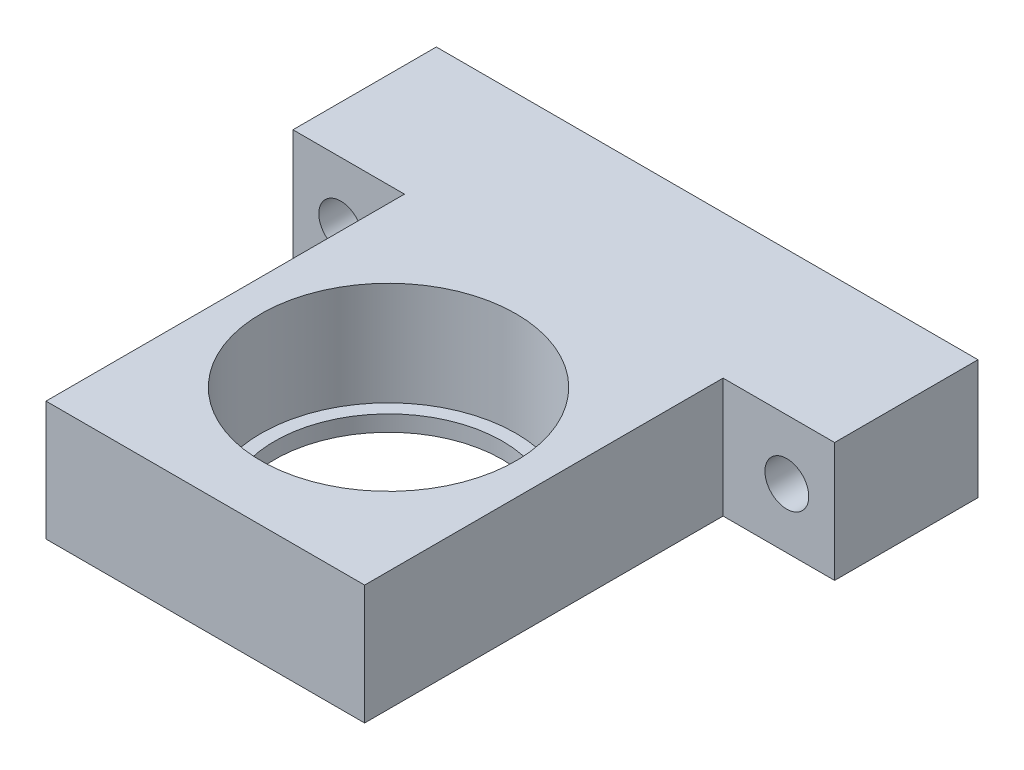
SolidWorks part; units mm, degrees
ref_plane "前视基准面" through (0, 0, 0) normal (0, 0, 1) x (1, 0, 0)
ref_plane "上视基准面" through (0, 0, 0) normal (0, 1, 0) x (1, 0, 0)
ref_plane "右视基准面" through (0, 0, 0) normal (1, 0, 0) x (0, 0, -1)
sketch "草图1" plane through (0, 0, 0) normal (0, 0, 1) x (1, 0, 0)
  line L1 (-34, 7.5) -> (34, 7.5)
  line L2 (-34, 7.5) -> (-34, -7.5)
  line L3 (-34, -7.5) -> (34, -7.5)
  line L4 (34, 7.5) -> (34, -7.5)
  line L5 (0, -7.5) -> (0, 7.5) construction
  line L6 (-34, 0) -> (34, 0) construction
  point P0 (0, 0)
  dimension "D1" = 15
  dimension "D2" = 68
extrude "凸台-拉伸1" add sketch "草图1" along normal blind 18
sketch "草图2" plane through (0, 0, 18) normal (0, 0, 1) x (1, 0, 0)
  line L0 (-34, -7.5) -> (34, -7.5) construction
  line L1 (-20, 7.5) -> (20, 7.5)
  line L2 (-20, 7.5) -> (-20, -7.5)
  line L3 (-20, -7.5) -> (20, -7.5)
  line L4 (20, 7.5) -> (20, -7.5)
  line L5 (0, -7.5) -> (0, 7.5) construction
  line L6 (-20, 0) -> (20, 0) construction
  point P0 (0, 0)
  dimension "D1" = 40
extrude "凸台-拉伸2" add sketch "草图2" along normal blind 45
sketch "草图3" plane through (0, -7.5, 0) normal (0, -1, 0) x (1, 0, 0)
  circle A0 centre (0, 40) radius 16
  dimension "D2" = 32
  dimension "D1" = 40
extrude "切除-拉伸1" cut sketch "草图3" against normal blind 43
sketch "草图4" plane through (0, -7.5, 0) normal (0, -1, 0) x (1, 0, 0)
  circle A0 centre (0, 40) radius 16
  circle A1 centre (0, 40) radius 14.3
  dimension "D1" = 28.6
extrude "凸台-拉伸3" add sketch "草图4" against normal blind 2
sketch "草图5" plane through (0, 0, 18) normal (0, 0, 1) x (1, 0, 0)
  circle A0 centre (28, 0) radius 2.75
  circle A1 centre (-28, 0) radius 2.75
  point P4 (0, 0)
  dimension "D3" = 5.5
  dimension "D4" = 5.5
  dimension "D1" = 28
  dimension "D2" = 28
extrude "切除-拉伸2" cut sketch "草图5" against normal blind 21
